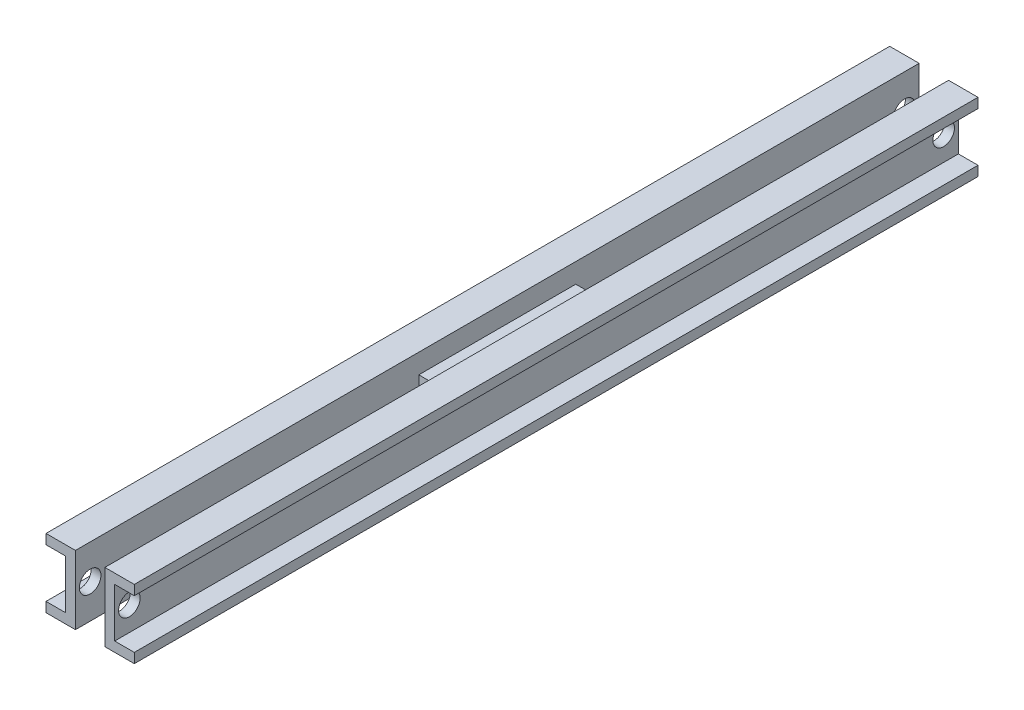
SolidWorks part; units mm, degrees
ref_plane "Front Plane" through (0, 0, 0) normal (0, 0, 1) x (1, 0, 0)
ref_plane "Top Plane" through (0, 0, 0) normal (0, 1, 0) x (1, 0, 0)
ref_plane "Right Plane" through (0, 0, 0) normal (1, 0, 0) x (0, 0, -1)
sketch "Sketch1" plane through (0, 0, 0) normal (0, 0, 1) x (1, 0, 0)
  line L1 (15, 15) -> (-15, 15)
  line L3 (15, -15) -> (-15, -15)
  line L5 (0, 0) -> (-15, -15) construction
  line L6 (15, -15) -> (0, 0) construction
  line L24 (-45, -25) -> (-45, -35)
  line L25 (-15, 35) -> (-45, 35)
  line L26 (-15, 35) -> (-15, 15)
  line L27 (-15, -35) -> (-45, -35)
  line L28 (-45, 35) -> (-45, 25)
  line L29 (15, 35) -> (45, 35)
  line L30 (15, 35) -> (15, 15)
  line L31 (15, -35) -> (45, -35)
  line L32 (45, 35) -> (45, 25)
  line L33 (45, 25) -> (25, 25)
  line L35 (45, -25) -> (25, -25)
  line L36 (25, 25) -> (25, -25)
  line L37 (-45, 25) -> (-25, 25)
  line L39 (-45, -25) -> (-25, -25)
  line L40 (-25, 25) -> (-25, -25)
  line L41 (45, -25) -> (45, -35)
  line L42 (-15, -15) -> (-15, -35)
  line L43 (15, -15) -> (15, -35)
  point P0 (0, 0)
  point P23 (0, 0)
  point P24 (0, 0)
  point P25 (-42.4, -23.6)
  point P26 (45, -23.2)
  dimension "D1" = 15
  dimension "D2" = 15
  dimension "D3" = 15
  dimension "D4" = 15
  dimension "D5" = 30
  dimension "D6" = 10
  dimension "D7" = 10
  dimension "D8" = 10
  dimension "D9" = 30
  dimension "D10" = 10
  dimension "D11" = 10
  dimension "D12" = 10
  dimension "D13" = 20
  dimension "D14" = 20
  dimension "D15" = 20
  dimension "D16" = 20
extrude "Boss-Extrude1" add sketch "Sketch1" along normal mid plane 160
sketch "Sketch2" plane through (0, 0, 80) normal (0, 0, 1) x (1, 0, 0)
  line L0 (-45, -25) -> (-45, -35)
  line L1 (-45, 35) -> (-15, 35)
  line L2 (-45, 35) -> (-45, 25)
  line L3 (-45, -35) -> (-15, -35)
  line L4 (-15, 35) -> (-15, -35)
  line L5 (-45, 25) -> (-25, 25)
  line L7 (-45, -25) -> (-25, -25)
  line L8 (-25, 25) -> (-25, -25)
  line L9 (15, 35) -> (45, 35)
  line L10 (15, 35) -> (15, -35)
  line L11 (15, -35) -> (45, -35)
  line L12 (45, 35) -> (45, 25)
  line L13 (45, 25) -> (25, 25)
  line L15 (45, -25) -> (25, -25)
  line L16 (25, 25) -> (25, -25)
  line L17 (45, -25) -> (45, -35)
extrude "Boss-Extrude2" add sketch "Sketch2" along normal blind 350
sketch "Sketch3" plane through (0, 0, -80) normal (0, 0, -1) x (-1, 0, 0)
  line L0 (-45, -25) -> (-45, -35)
  line L1 (-45, 35) -> (-15, 35)
  line L2 (-45, 35) -> (-45, 25)
  line L3 (-45, -35) -> (-15, -35)
  line L4 (-15, 35) -> (-15, -35)
  line L5 (45, 35) -> (15, 35)
  line L6 (45, 35) -> (45, 25)
  line L7 (45, -35) -> (15, -35)
  line L8 (15, 35) -> (15, -35)
  line L9 (25, 25) -> (45, 25)
  line L10 (25, 25) -> (25, -25)
  line L11 (25, -25) -> (45, -25)
  line L13 (-45, 25) -> (-25, 25)
  line L15 (-45, -25) -> (-25, -25)
  line L16 (-25, 25) -> (-25, -25)
  line L17 (45, -25) -> (45, -35)
extrude "Boss-Extrude3" add sketch "Sketch3" along normal blind 350
sketch "Sketch4" plane through (-25, 0, 0) normal (-1, 0, 0) x (0, 0, 1)
  line L0 (430, 25) -> (430, -25) construction
  line L1 (-430, -25) -> (-430, 25) construction
  circle A0 centre (-415, 0) radius 11
  circle A1 centre (415, 0) radius 11
  dimension "D1" = 22
  dimension "D2" = 22
  dimension "D3" = 15
  dimension "D4" = 15
  dimension "D5" = 25
  dimension "D6" = 25
extrude "Cut-Extrude1" cut sketch "Sketch4" against normal blind 350
